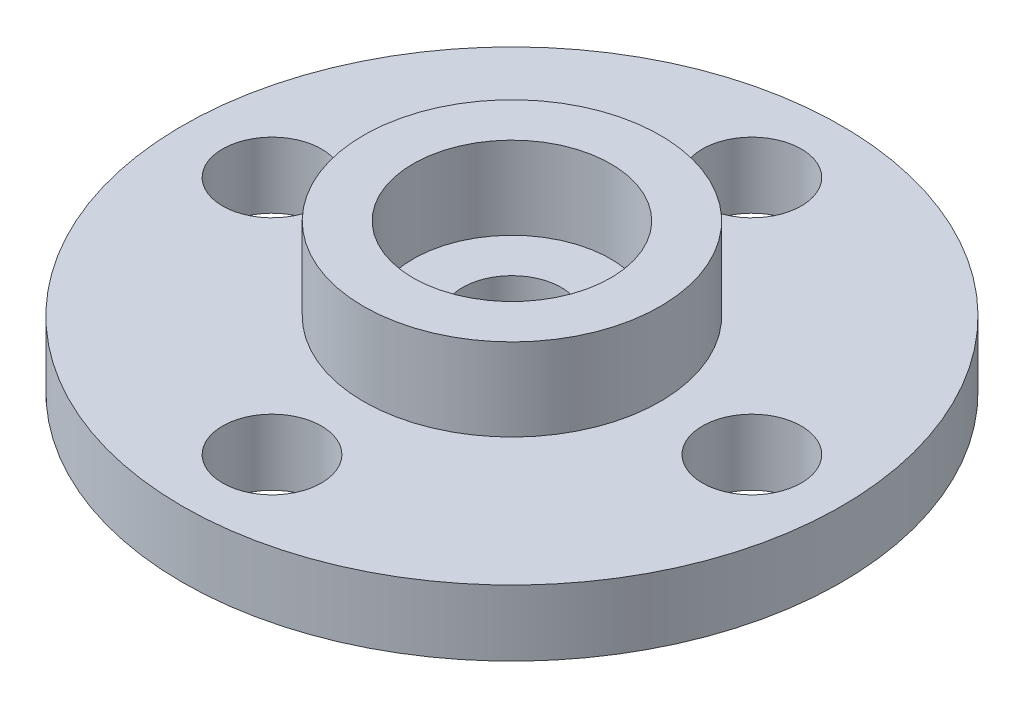
SolidWorks part; units mm, degrees
ref_plane "Alzado" through (0, 0, 0) normal (0, 0, 1) x (1, 0, 0)
ref_plane "Planta" through (0, 0, 0) normal (0, 1, 0) x (1, 0, 0)
ref_plane "Vista lateral" through (0, 0, 0) normal (1, 0, 0) x (0, 0, -1)
sketch "Croquis1" plane through (0, 0, 0) normal (0, 1, 0) x (1, 0, 0)
  circle A0 centre (0, 0) radius 10
  dimension "D1" = 20
extrude "Saliente-Extruir1" add sketch "Croquis1" along normal blind 2
sketch "Croquis2" plane through (0, 2, 0) normal (0, 1, 0) x (1, 0, 0)
  circle A0 centre (0, 0) radius 4.5
  dimension "D1" = 9
extrude "Saliente-Extruir2" add sketch "Croquis2" along normal blind 2.5
sketch "Croquis3" plane through (0, 4.5, 0) normal (0, 1, 0) x (1, 0, 0)
  circle A0 centre (0, 0) radius 3
  dimension "D1" = 6
extrude "Cortar-Extruir1" cut sketch "Croquis3" against normal blind 2.5
sketch "Croquis4" plane through (0, 2, 0) normal (0, 1, 0) x (1, 0, 0)
  circle A0 centre (0, 0) radius 1.5
  circle A1 centre (0, 7.28) radius 1.5
  circle A2 centre (7.28, 0) radius 1.5
  circle A3 centre (0, -7.28) radius 1.5
  circle A4 centre (-7.28, 0) radius 1.5
  point P14 (0, 0)
  dimension "D1" = 3
  dimension "D2" = 3
  dimension "D3" = 7.28
  dimension "D5" = 7.28
  dimension "D4" = 4
extrude "Cortar-Extruir2" cut sketch "Croquis4" against normal blind 2.5
